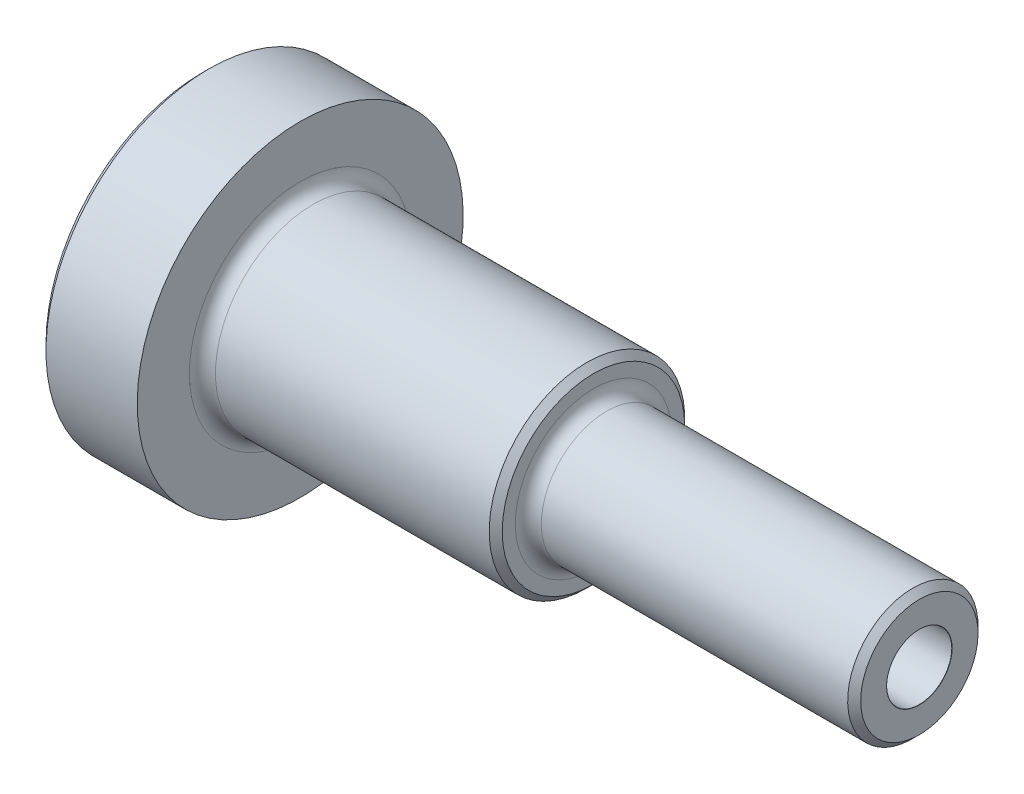
SolidWorks part; units mm, degrees
ref_plane "Plano frontal" through (0, 0, 0) normal (0, 0, 1) x (1, 0, 0)
ref_plane "Plano superior" through (0, 0, 0) normal (0, 1, 0) x (1, 0, 0)
ref_plane "Plano direito" through (0, 0, 0) normal (1, 0, 0) x (0, 0, -1)
sketch "Esboço1" plane through (0, 0, 0) normal (0, 0, 1) x (1, 0, 0)
  line L0 (0, 0) -> (0, 25)
  line L1 (0, 25) -> (15, 25)
  line L2 (15, 25) -> (15, 15)
  line L3 (15, 15) -> (60, 15)
  line L4 (60, 15) -> (60, 10)
  line L5 (60, 10) -> (110, 10)
  line L6 (110, 10) -> (110, 0)
  line L7 (110, 0) -> (0, 0) construction
  line L8 (0, 0) -> (110, 0)
  dimension "D1" = 15
  dimension "D2" = 45
  dimension "D3" = 50
  dimension "D4" = 50
  dimension "D5" = 30
  dimension "D6" = 20
revolve "Revolução1" add sketch "Esboço1" angle 360 about L7
hole_wizard "Furos-guia com Ø10.0mm1" positions "Esboço2" profile "Esboço3" hole size "Ø10.0" standard "DIN" end condition through all
sketch "Esboço2" plane through (110, 0, 0) normal (1, 0, 0) x (0, 0, -1)
  point P0 (0, 0)
sketch "Esboço3" plane through (110, 0, 0) normal (0, 1, 0) x (0, 0, -1)
  line L0 (0, 0) -> (0, 110)
  line L1 (0, 110) -> (5, 110)
  line L2 (5, 110) -> (5, 0.025)
  line L3 (5, 0.025) -> (5.025, 0)
  line L5 (5.025, 0) -> (0, 0)
  line L6 (-5, 0.025) -> (-5.025, 0) construction
  line L11 (0, -6.35) -> (0, 107.95) construction
  dimension "Thru Hole Dia." = 10
  dimension "Thru Hole Depth" = 110
  dimension "Near C'Sink Dia." = 10.05
  dimension "Near C'Sink Angle" = 90
fillet "Filete1" radius 2 2 edges at (60, 10, 0) (15, 15, 0)
chamfer "Chanfro4" distance 1 angle 45 3 edges at (110, 10, 0) (60, 15, 0) (0, 25, 0)
chamfer "Chanfro6" distance 1 angle 45 1 edges at (0, 0, -5)
